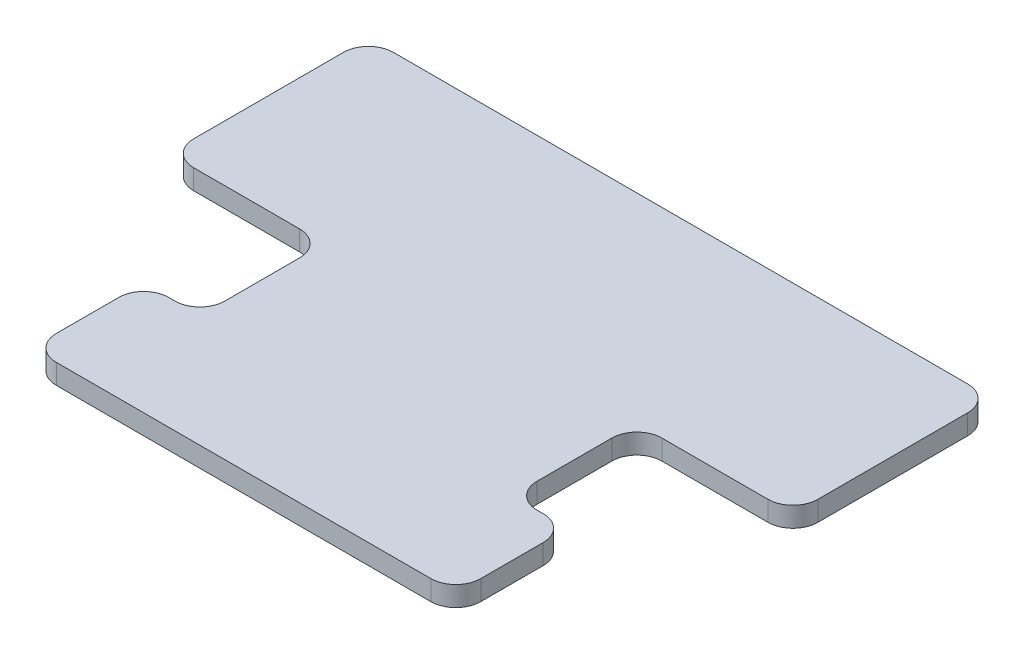
SolidWorks part; units mm, degrees
ref_plane "정면" through (0, 0, 0) normal (0, 0, 1) x (1, 0, 0)
ref_plane "윗면" through (0, 0, 0) normal (0, 1, 0) x (1, 0, 0)
ref_plane "우측면" through (0, 0, 0) normal (1, 0, 0) x (0, 0, -1)
sketch "스케치1" plane through (0, 0, 0) normal (0, 1, 0) x (1, 0, 0)
  line L0 (87.3787, 0) -> (12.5, 0) construction
  line L1 (0, 54.1284) -> (0, -54.3861) construction
  line L2 (14.5, -0.0265) -> (23, -0.0265)
  line L3 (-15, -10.0265) -> (-14.5, -10.0265)
  line L4 (-17, -12.0265) -> (-17, -17.0265)
  line L5 (-23, 15.9735) -> (23, 15.9735)
  line L6 (-25, 13.9735) -> (-25, 1.9735)
  line L7 (-23, -0.0265) -> (-14.5, -0.0265)
  line L8 (25, 13.9735) -> (25, 1.9735)
  line L9 (-25, 15.9735) -> (25, -0.0265) construction
  line L10 (-25, -0.0265) -> (25, 15.9735) construction
  line L11 (-15, -19.0265) -> (15, -19.0265)
  line L12 (17, -12.0265) -> (17, -17.0265)
  line L13 (-17, -10.0265) -> (17, -19.0265) construction
  line L14 (-17, -19.0265) -> (17, -10.0265) construction
  line L16 (-12.5, -2.0265) -> (-12.5, -8.0265)
  line L18 (12.5, -2.0265) -> (12.5, -8.0265)
  line L19 (-5.2577, 0) -> (-88.9252, 0) construction
  line L20 (14.5, -10.0265) -> (15, -10.0265)
  arc A0 (-23, 15.9735) -> (-25, 13.9735) centre (-23, 13.9735) ccw
  arc A1 (-17, -17.0265) -> (-15, -19.0265) centre (-15, -17.0265) ccw
  arc A2 (-15, -10.0265) -> (-17, -12.0265) centre (-15, -12.0265) ccw
  arc A3 (23, -0.0265) -> (25, 1.9735) centre (23, 1.9735) ccw
  arc A4 (23, 15.9735) -> (25, 13.9735) centre (23, 13.9735) cw
  arc A5 (-25, 1.9735) -> (-23, -0.0265) centre (-23, 1.9735) ccw
  arc A6 (14.5, -10.0265) -> (12.5, -8.0265) centre (14.5, -8.0265) cw
  arc A7 (14.5, -0.0265) -> (12.5, -2.0265) centre (14.5, -2.0265) ccw
  arc A8 (-14.5, -0.0265) -> (-12.5, -2.0265) centre (-14.5, -2.0265) cw
  arc A9 (15, -19.0265) -> (17, -17.0265) centre (15, -17.0265) ccw
  arc A10 (15, -10.0265) -> (17, -12.0265) centre (15, -12.0265) cw
  arc A11 (-12.5, -8.0265) -> (-14.5, -10.0265) centre (-14.5, -8.0265) cw
  point P3 (0, -14.5265)
  point P8 (0, 7.9735)
  point P41 (12.5, -10.0265)
  point P44 (12.5, -0.0265)
  point P47 (-12.5, -0.0265)
  point P51 (0, 0)
  dimension "D9" = 2
  dimension "D10" = 2
  dimension "D11" = 2
  dimension "D12" = 2
  dimension "D13" = 2
  dimension "D1" = 50
  dimension "D2" = 16
  dimension "D3" = 10
  dimension "D4" = 9
  dimension "D5" = 12.5
  dimension "D6" = 12.5
  dimension "D7" = 17
  dimension "D8" = 17
extrude "보스-돌출2" add sketch "스케치1" along normal blind 1.6 contours L7 A8 L16 A11 L3 A2 L4 A1 L11 A9 L12 A10 L20 A6 L18 A7 L2 A3 L8 A4 L5 A0 L6 A5
